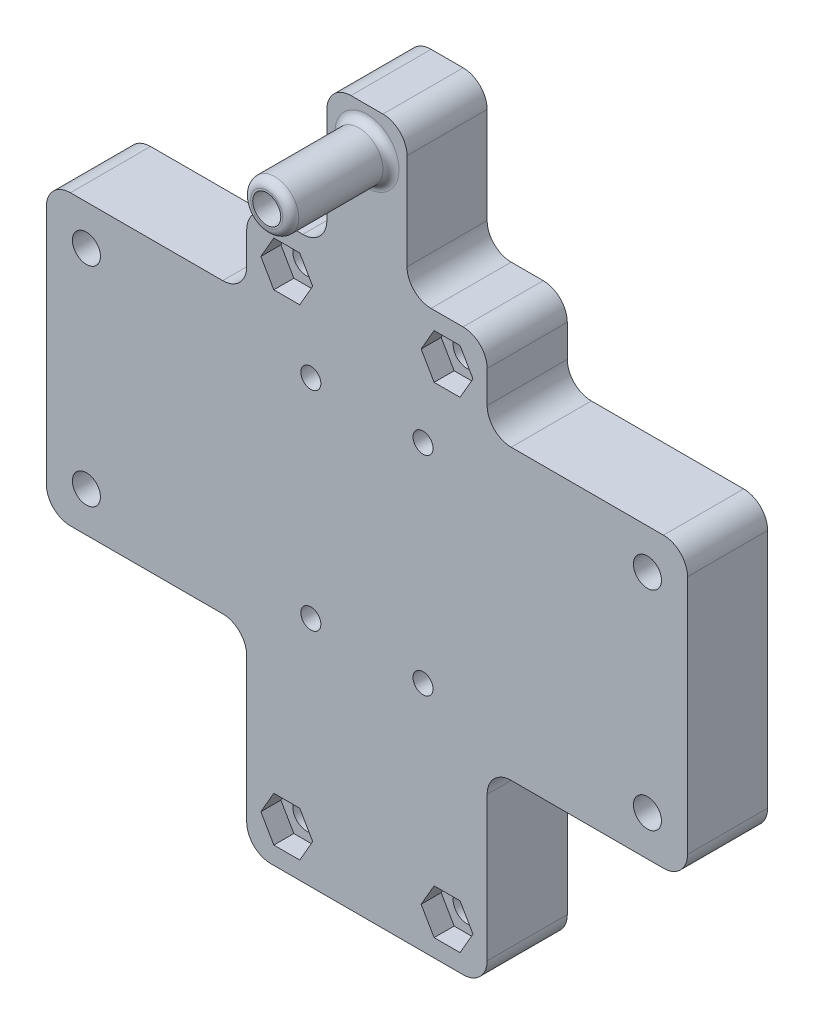
SolidWorks part; units mm, degrees
ref_plane "正面" through (0, 0, 0) normal (0, 0, 1) x (1, 0, 0)
ref_plane "平面" through (0, 0, 0) normal (0, 1, 0) x (1, 0, 0)
ref_plane "右側面" through (0, 0, 0) normal (1, 0, 0) x (0, 0, -1)
sketch "ｽｹｯﾁ2" plane through (0, 0, 0) normal (0, 0, 1) x (1, 0, 0)
  line L0 (0, 18) -> (0, -18) construction
  line L1 (40, 18) -> (-40, 18)
  line L2 (40, 18) -> (40, -18)
  line L3 (40, -18) -> (-40, -18)
  line L4 (-40, 18) -> (-40, -18)
  line L5 (40, 18) -> (-40, -18) construction
  line L6 (40, -18) -> (-40, 18) construction
  line L7 (-38.0626, 0) -> (40, 0) construction
  line L8 (-40, -7) -> (40, -7)
  line L9 (0, 18) -> (0, 32) construction
  line L10 (15, 28) -> (-15, 28)
  line L11 (15, 28) -> (15, -42)
  line L12 (15, -42) -> (-15, -42)
  line L13 (-15, 28) -> (-15, -42)
  line L14 (15, 28) -> (-15, -42) construction
  line L15 (15, -42) -> (-15, 28) construction
  line L17 (5, 46) -> (-5, 46)
  line L18 (5, 46) -> (5, 18)
  line L19 (5, 18) -> (-5, 18)
  line L20 (-5, 46) -> (-5, 18)
  line L21 (5, 46) -> (-5, 18) construction
  line L22 (5, 18) -> (-5, 46) construction
  circle A0 centre (-35, 13) radius 1.75
  circle A1 centre (-7, 13) radius 1.25
  circle A2 centre (7, 13) radius 1.25
  circle A3 centre (35, 13) radius 1.75
  circle A4 centre (35, -13) radius 1.75
  circle A5 centre (7, -13) radius 1.25
  circle A6 centre (-7, -13) radius 1.25
  circle A7 centre (-35, -13) radius 1.75
  circle A8 centre (-10, 23) radius 1.75
  circle A9 centre (10, 23) radius 1.75
  circle A10 centre (10, -37) radius 1.75
  circle A11 centre (-10, -37) radius 1.75
  circle A12 centre (0, 41) radius 1.75
  point P0 (0, 0)
  point P28 (0, -7)
  dimension "D3" = 3.5
  dimension "D4" = 13
  dimension "D6" = 2.5
  dimension "D7" = 7
  dimension "D8" = 13
  dimension "D12" = 30
  dimension "D13" = 10
  dimension "D14" = 3.5
  dimension "D17" = 3.5
  dimension "D18" = 5
  dimension "D1" = 36
  dimension "D2" = 80
  dimension "D5" = 5
  dimension "D9" = 20
  dimension "D10" = 30
  dimension "D11" = 70
  dimension "D15" = 14
  dimension "D16" = 10
extrude "ﾎﾞｽ - 押し出し1" add sketch "ｽｹｯﾁ2" along normal blind 10 contours L13 L1 L4 L8 A0 | L13 L8 L4 L3 A7 | L8 L13 L3 L11 A5 A6 | L1 L13 L8 L11 A1 A2 | L1 L11 L8 L2 A3 | L8 L11 L3 L2 A4 | L3 L13 L12 L11 A10 A11 | L20 L10 L13 L1 A8 | L10 L20 L1 L18 | L10 L18 L1 L11 A9 | L17 L20 L10 L18 A12
sketch "ｽｹｯﾁ4" plane through (0, 0, 0) normal (0, 0, -1) x (-1, 0, 0)
  line L0 (0, 46) -> (0, -42) construction
  line L1 (-5, 46) -> (5, 46) construction
  line L2 (-15, -42) -> (15, -42) construction
  line L3 (-40, 0) -> (40, 0) construction
  line L4 (-40, 18) -> (-40, -18) construction
  line L5 (40, 18) -> (40, -18) construction
  circle A0 centre (-35, 13) radius 3.2
  circle A2 centre (35, 13) radius 3.2
  circle A3 centre (35, -13) radius 3.2
  circle A4 centre (-35, -13) radius 3.2
  dimension "D1" = 6.4
extrude "ｶｯﾄ - 押し出し2" cut sketch "ｽｹｯﾁ4" against normal blind 2.5
sketch "ｽｹｯﾁ5" plane through (0, 0, 0) normal (0, 0, -1) x (-1, 0, 0)
  line L0 (0, 46) -> (0, -42) construction
  line L1 (-5, 46) -> (5, 46) construction
  line L2 (-15, -42) -> (15, -42) construction
  line L3 (40, 0) -> (-40, 0) construction
  line L4 (40, 18) -> (40, -18) construction
  line L5 (-40, 18) -> (-40, -18) construction
  circle A0 centre (-7, 13) radius 2.2
  circle A1 centre (7, 13) radius 2.2
  circle A2 centre (7, -13) radius 2.2
  circle A3 centre (-7, -13) radius 2.2
  dimension "D1" = 4.4
extrude "ｶｯﾄ - 押し出し3" cut sketch "ｽｹｯﾁ5" against normal blind 2
fillet "ﾌｨﾚｯﾄ2" radius 3 16 edges at (-40, -18, 5) (-15, -18, 5) (-15, -42, 5) (15, -42, 5) (15, -18, 5) (40, -18, 5) (40, 18, 5) (15, 18, 5) (15, 28, 5) (5, 28, 5) (5, 46, 5) (-5, 46, 5) (-5, 28, 5) (-15, 28, 5) (-40, 18, 5) (-15, 18, 5)
sketch "ｽｹｯﾁ6" plane through (0, 0, 0) normal (0, 0, -1) x (-1, 0, 0)
  line L1 (3.2332, 41) -> (1.6166, 43.8)
  line L2 (1.6166, 43.8) -> (-1.6166, 43.8)
  line L3 (-1.6166, 43.8) -> (-3.2332, 41)
  line L4 (-3.2332, 41) -> (-1.6166, 38.2)
  line L5 (-1.6166, 38.2) -> (1.6166, 38.2)
  line L6 (1.6166, 38.2) -> (3.2332, 41)
  circle A0 centre (0, 41) radius 2.8 construction
  dimension "D1" = 5.6
extrude "ｶｯﾄ - 押し出し4" cut sketch "ｽｹｯﾁ6" against normal blind 2.5 contours L6 L1 L2 L3 L4 L5
sketch "ｽｹｯﾁ7" plane through (0, 0, 10) normal (0, 0, 1) x (1, 0, 0)
  line L0 (0, 0) -> (0, 41) construction
  line L1 (-6.7668, 23) -> (-8.3834, 25.8)
  line L2 (-8.3834, 25.8) -> (-11.6166, 25.8)
  line L3 (-11.6166, 25.8) -> (-13.2332, 23)
  line L4 (-13.2332, 23) -> (-11.6166, 20.2)
  line L5 (-11.6166, 20.2) -> (-8.3834, 20.2)
  line L6 (-8.3834, 20.2) -> (-6.7668, 23)
  line L7 (0, 0) -> (40, 0) construction
  line L8 (40, 15) -> (40, -15) construction
  line L9 (8.3834, 20.2) -> (6.7668, 23)
  line L10 (11.6166, 20.2) -> (8.3834, 20.2)
  line L11 (13.2332, 23) -> (11.6166, 20.2)
  line L12 (11.6166, 25.8) -> (13.2332, 23)
  line L13 (8.3834, 25.8) -> (11.6166, 25.8)
  line L14 (6.7668, 23) -> (8.3834, 25.8)
  line L15 (8.3834, -39.8) -> (6.7668, -37)
  line L16 (-6.7668, -37) -> (-8.3834, -34.2)
  line L17 (-8.3834, -34.2) -> (-11.6166, -34.2)
  line L18 (-11.6166, -34.2) -> (-13.2332, -37)
  line L19 (-13.2332, -37) -> (-11.6166, -39.8)
  line L20 (-11.6166, -39.8) -> (-8.3834, -39.8)
  line L21 (-8.3834, -39.8) -> (-6.7668, -37)
  line L22 (11.6166, -39.8) -> (8.3834, -39.8)
  line L23 (13.2332, -37) -> (11.6166, -39.8)
  line L24 (11.6166, -34.2) -> (13.2332, -37)
  line L25 (8.3834, -34.2) -> (11.6166, -34.2)
  line L26 (6.7668, -37) -> (8.3834, -34.2)
  circle A0 centre (-10, 23) radius 2.8 construction
  circle A1 centre (10, 23) radius 2.8 construction
  circle A2 centre (-10, -37) radius 2.8 construction
  circle A3 centre (10, -37) radius 2.8 construction
  dimension "D2" = 5.6
  dimension "D1" = 5.6
extrude "ｶｯﾄ - 押し出し5" cut sketch "ｽｹｯﾁ7" against normal blind 2.5
sketch "ｽｹｯﾁ8" plane through (0, 0, 10) normal (0, 0, 1) x (1, 0, 0)
  circle A0 centre (0, 41) radius 1.75
  circle A1 centre (0, 41) radius 3
  dimension "D1" = 6
extrude "ﾎﾞｽ - 押し出し2" add sketch "ｽｹｯﾁ8" along normal blind 12.5
fillet "ﾌｨﾚｯﾄ3" radius 1 2 edges at (3, 41, 22.5) (3, 41, 10)
